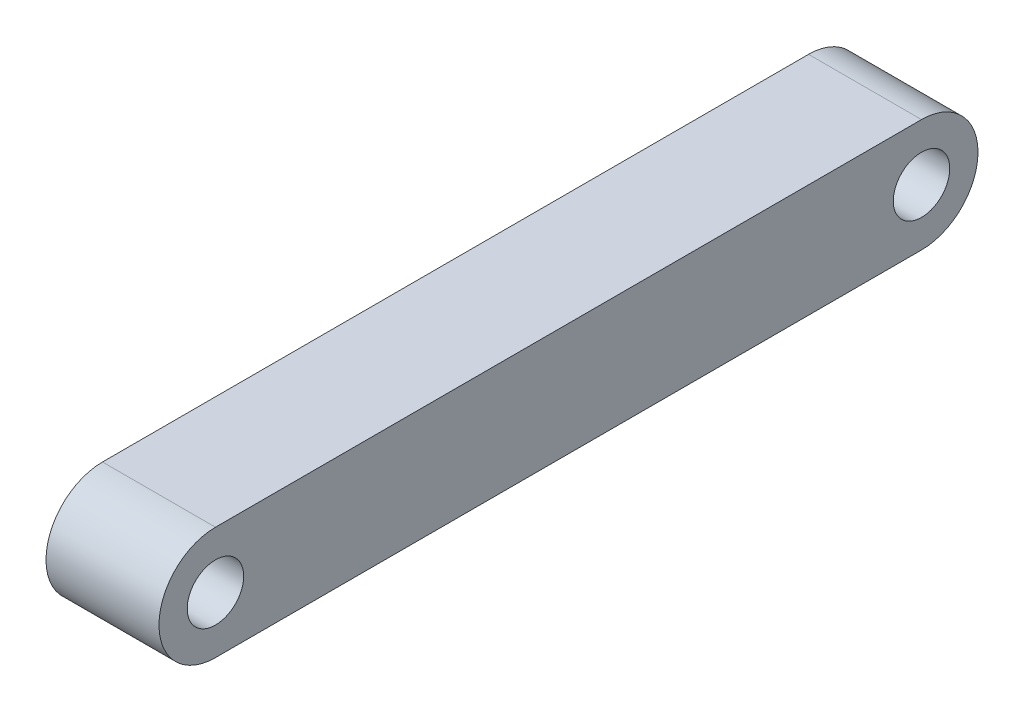
SolidWorks part; units mm, degrees
ref_plane "Front Plane" through (0, 0, 0) normal (0, 0, 1) x (1, 0, 0)
ref_plane "Top Plane" through (0, 0, 0) normal (0, 1, 0) x (1, 0, 0)
ref_plane "Right Plane" through (0, 0, 0) normal (1, 0, 0) x (0, 0, -1)
sketch "Sketch1" plane through (0, 0, 0) normal (1, 0, 0) x (0, 0, -1)
  line L1 (0, -20) -> (250, -20)
  line L2 (0, -20) -> (0, 20)
  line L3 (0, 20) -> (250, 20)
  line L4 (250, -20) -> (250, 20)
  circle A0 centre (0, 0) radius 10
  circle A1 centre (0, 0) radius 20
  circle A2 centre (250, 0) radius 10
  circle A3 centre (250, 0) radius 20
  point P11 (0, 0)
  point P12 (250, 0)
  point P13 (156.728, 5.5968)
  point P14 (125.3377, 0)
  dimension "D1" = 20
  dimension "D2" = 40
  dimension "D3" = 250
extrude "Boss-Extrude1" add sketch "Sketch1" along normal mid plane 40 contours L2 A1 A0 | L2 A1 A0 | A3 L3 A1 L1 | L4 A3 A2 | L4 A3 A2
